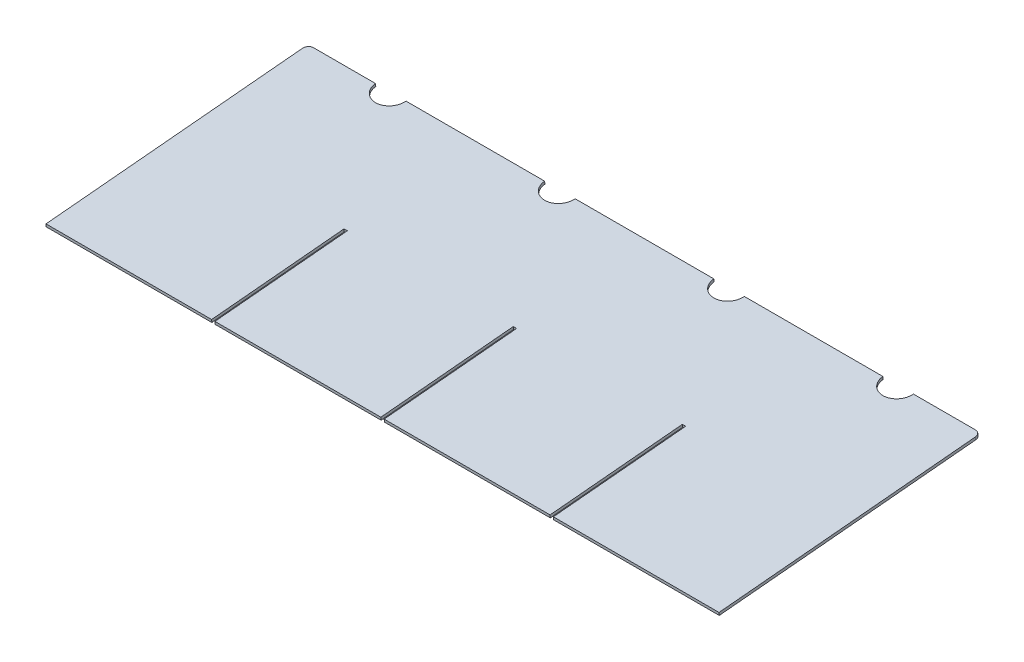
SolidWorks part; units mm, degrees
ref_plane "前视基准面" through (0, 0, 0) normal (0, 0, 1) x (1, 0, 0)
ref_plane "上视基准面" through (0, 0, 0) normal (0, 1, 0) x (1, 0, 0)
ref_plane "右视基准面" through (0, 0, 0) normal (1, 0, 0) x (0, 0, -1)
ref_plane "基准面1" through (0, 53.9331, 5.0103) normal (0, 0.9957, 0.0925) x (-1, 0, 0)
sketch "草图1" plane through (0, 53.9331, 5.0103) normal (0, 0.9957, 0.0925) x (-1, 0, 0)
  line L0 (-121.5, 905.5938) -> (-121.5, 812.5938)
  line L1 (-119.5, 810.5938) -> (-97.1, 810.5938)
  line L2 (-86.1, 810.5938) -> (-36.05, 810.5938)
  line L3 (-25.05, 810.5938) -> (25.05, 810.5938)
  line L4 (36.05, 810.5938) -> (86.1, 810.5938)
  line L5 (97.1, 810.5938) -> (119.5, 810.5938)
  line L6 (121.5, 812.5938) -> (121.5, 905.5938)
  line L7 (121.5, 905.5938) -> (61.7, 905.5938)
  line L8 (61.7, 905.5938) -> (61.7, 857.5838)
  line L9 (61.7, 857.5838) -> (60.5, 857.5938)
  line L10 (60.5, 857.5938) -> (60.5, 905.5938)
  line L11 (60.5, 905.5938) -> (0.6, 905.5938)
  line L12 (0.6, 905.5938) -> (0.6, 857.5938)
  line L13 (0.6, 857.5938) -> (-0.6, 857.5938)
  line L14 (-0.6, 857.5938) -> (-0.6, 905.5938)
  line L15 (-0.6, 905.5938) -> (-60.5, 905.5938)
  line L16 (-60.5, 905.5938) -> (-60.5, 857.6035)
  line L17 (-60.5, 857.6035) -> (-61.7, 857.5938)
  line L18 (-61.7, 857.5938) -> (-61.7, 905.5938)
  line L19 (-61.7, 905.5938) -> (-121.5, 905.5938)
  arc A0 (-121.5, 812.5938) -> (-119.5, 810.5938) centre (-119.5, 812.5938) ccw
  arc A1 (-97.1, 810.5938) -> (-86.1, 810.5938) centre (-91.6, 810.5938) cw
  arc A2 (-36.05, 810.5938) -> (-25.05, 810.5938) centre (-30.55, 810.5938) cw
  arc A3 (25.05, 810.5938) -> (36.05, 810.5938) centre (30.55, 810.5938) cw
  arc A4 (86.1, 810.5938) -> (97.1, 810.5938) centre (91.6, 810.5938) cw
  arc A5 (119.5, 810.5938) -> (121.5, 812.5938) centre (119.5, 812.5938) ccw
extrude "凸台-拉伸1" add sketch "草图1" against normal blind 1
